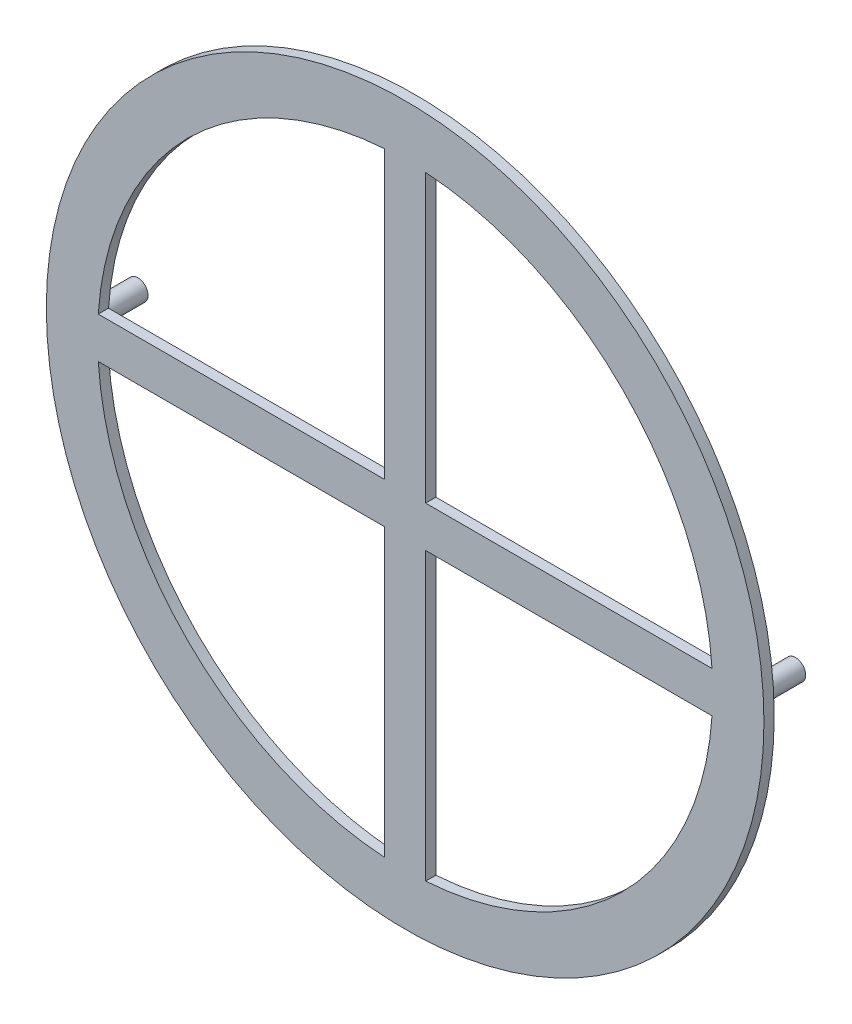
SolidWorks part; units mm, degrees
ref_plane "Front Plane" through (0, 0, 0) normal (0, 0, 1) x (1, 0, 0)
ref_plane "Top Plane" through (0, 0, 0) normal (0, 1, 0) x (1, 0, 0)
ref_plane "Right Plane" through (0, 0, 0) normal (1, 0, 0) x (0, 0, -1)
sketch "Sketch1" plane through (0, 0, 0) normal (0, 1, 0) x (1, 0, 0)
  line L0 (30, 1) -> (30, 0)
  line L1 (30, 0) -> (35, 0)
  line L3 (30, 1) -> (35, 1)
  line L4 (35, 0) -> (35, 1)
  line L5 (0, 0) -> (0, 6.5608) construction
  dimension "D1" = 5
  dimension "D2" = 1
  dimension "D3" = 0
  dimension "D4" = 30
revolve "Revolve1" add sketch "Sketch1" angle 360 about L5
sketch "Sketch2" plane through (0, 0, -1) normal (0, 0, -1) x (-1, 0, 0)
  line L1 (2, -30.9272) -> (-2, -30.9272)
  line L2 (2, -30.9272) -> (2, -2)
  line L3 (2, 30.9272) -> (-2, 30.9272)
  line L4 (-2, -30.9272) -> (-2, -2)
  line L5 (2, -30.9272) -> (0, 0) construction
  line L6 (2, 30.9272) -> (0.1293, 2) construction
  line L7 (31.2528, -2) -> (2, -2)
  line L8 (31.2528, -2) -> (31.2528, 2)
  line L9 (31.2528, 2) -> (2, 2)
  line L10 (-31.2528, -2) -> (-31.2528, 2)
  line L11 (31.2528, -2) -> (-31.2528, 2) construction
  line L12 (31.2528, 2) -> (-31.2528, -2) construction
  line L13 (-2, 2) -> (-31.2528, 2)
  line L14 (-2, 2) -> (-2, 30.9272)
  line L15 (-0.1293, 2) -> (-2, 30.9272) construction
  line L16 (0, 0) -> (-2, -30.9272) construction
  line L17 (-2, -0.128) -> (-2, 0.128)
  line L18 (-2, -2) -> (-31.2528, -2)
  line L19 (2, -0.128) -> (2, 0.128)
  line L20 (2, 2) -> (2, 30.9272)
  point P0 (0, 0)
  point P6 (0, 0)
  point P25 (0, 0)
  dimension "D1" = 4
  dimension "D2" = 4
extrude "Boss-Extrude1" add sketch "Sketch2" against normal blind 1
sketch "Sketch3" plane through (0, 0, -1) normal (0, 0, -1) x (-1, 0, 0)
  line L0 (0, 0) -> (0, 21.8851) construction
  circle A0 centre (-32.0719, 0) radius 2.9281 construction
  circle A1 centre (-32.0719, 0) radius 1
  circle A2 centre (32.0719, 0) radius 1
  dimension "D1" = 2
extrude "Boss-Extrude2" add sketch "Sketch3" along normal blind 5
